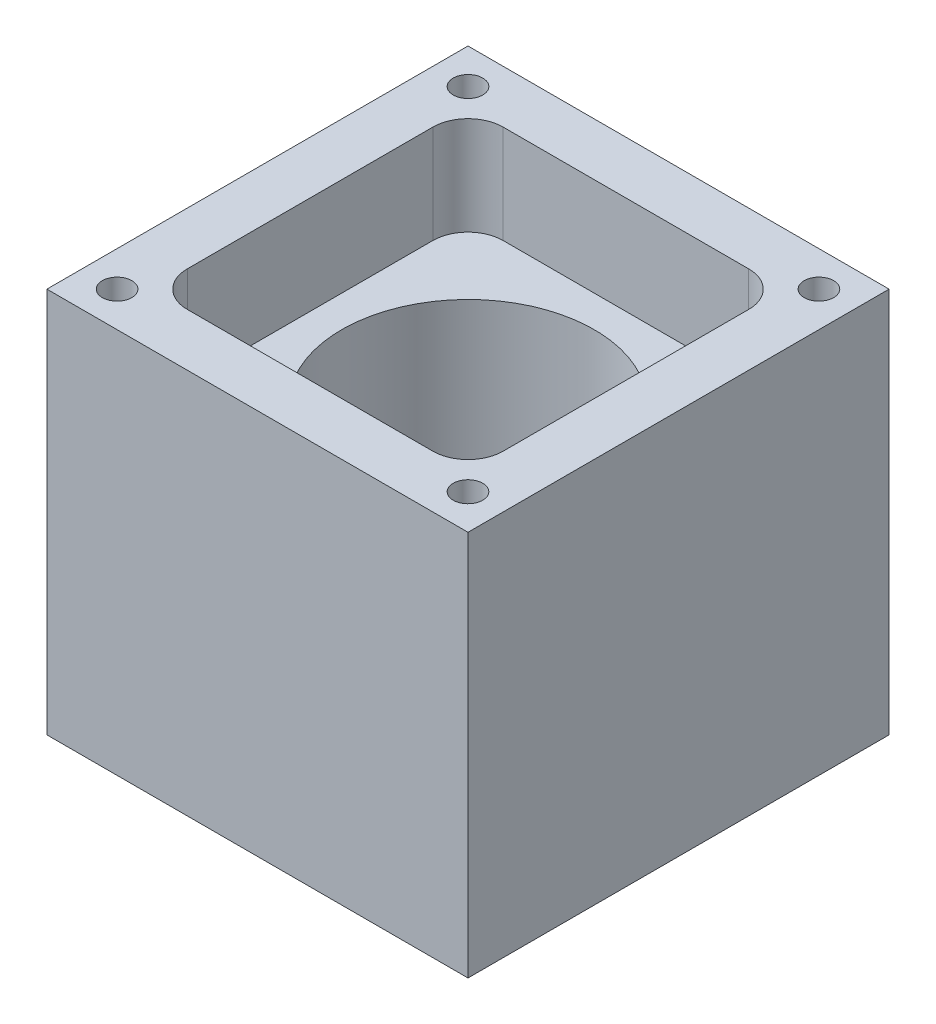
SolidWorks part; units mm, degrees
ref_plane "Front Plane" through (0, 0, 0) normal (0, 0, 1) x (1, 0, 0)
ref_plane "Top Plane" through (0, 0, 0) normal (0, 1, 0) x (1, 0, 0)
ref_plane "Right Plane" through (0, 0, 0) normal (1, 0, 0) x (0, 0, -1)
sketch "Sketch1" plane through (0, 0, 0) normal (0, 1, 0) x (1, 0, 0)
  line L1 (30, -30) -> (-30, -30)
  line L2 (30, -30) -> (30, 30)
  line L3 (30, 30) -> (-30, 30)
  line L4 (-30, -30) -> (-30, 30)
  line L5 (30, -30) -> (-30, 30) construction
  line L6 (30, 30) -> (-30, -30) construction
  point P0 (0, 0)
  dimension "D1" = 60
extrude "Boss-Extrude1" add sketch "Sketch1" along normal blind 55
sketch "Sketch2" plane through (0, 55, 0) normal (0, 1, 0) x (1, 0, 0)
  circle A0 centre (0, 0) radius 18
  dimension "D1" = 36
extrude "Cut-Extrude1" cut sketch "Sketch2" against normal through all
hole_wizard "M5 Tapped Hole1" positions "Sketch3" profile "Sketch4" tap size "M5" standard "ISO" end condition through all
sketch "Sketch3" plane through (0, 55, 0) normal (0, 1, 0) x (1, 0, 0)
  line L1 (25, -25) -> (-25, -25)
  line L2 (25, -25) -> (25, 25)
  line L3 (25, 25) -> (-25, 25)
  line L4 (-25, -25) -> (-25, 25)
  line L5 (25, -25) -> (-25, 25) construction
  line L6 (25, 25) -> (-25, -25) construction
  point P0 (-25, -25)
  point P2 (-25, 25)
  point P4 (25, 25)
  point P6 (25, -25)
  point P9 (0, 0)
  dimension "D1" = 50
sketch "Sketch4" plane through (-25, 55, 25) normal (1, 0, 0) x (0, 0, 1)
  line L0 (0, 0) -> (0, 55)
  line L1 (0, 55) -> (2.1, 55)
  line L2 (2.1, 55) -> (2.1, 0)
  line L5 (2.1, 0) -> (0, 0)
  line L11 (0, -6.35) -> (0, 107.95) construction
  dimension "Thru Tap Drill Dia." = 4.2
  dimension "Thru Tap Drill Depth" = 55
cosmetic thread "Hole Thread1" parameters "D2"=5
cosmetic thread "Hole Thread2" parameters "D2"=5
cosmetic thread "Hole Thread3" parameters "D2"=5
cosmetic thread "Hole Thread4" parameters "D2"=5
sketch "Sketch5" plane through (0, 55, 0) normal (0, 1, 0) x (1, 0, 0)
  line L1 (22.5, -22.5) -> (-22.5, -22.5)
  line L2 (22.5, -22.5) -> (22.5, 22.5)
  line L3 (22.5, 22.5) -> (-22.5, 22.5)
  line L4 (-22.5, -22.5) -> (-22.5, 22.5)
  line L5 (22.5, -22.5) -> (-22.5, 22.5) construction
  line L6 (22.5, 22.5) -> (-22.5, -22.5) construction
  point P0 (0, 0)
  dimension "D1" = 45
extrude "Cut-Extrude2" cut sketch "Sketch5" against normal blind 14
fillet "Fillet1" radius 5 4 edges at (22.5, 48, -22.5) (22.5, 48, 22.5) (-22.5, 48, 22.5) (-22.5, 48, -22.5)
